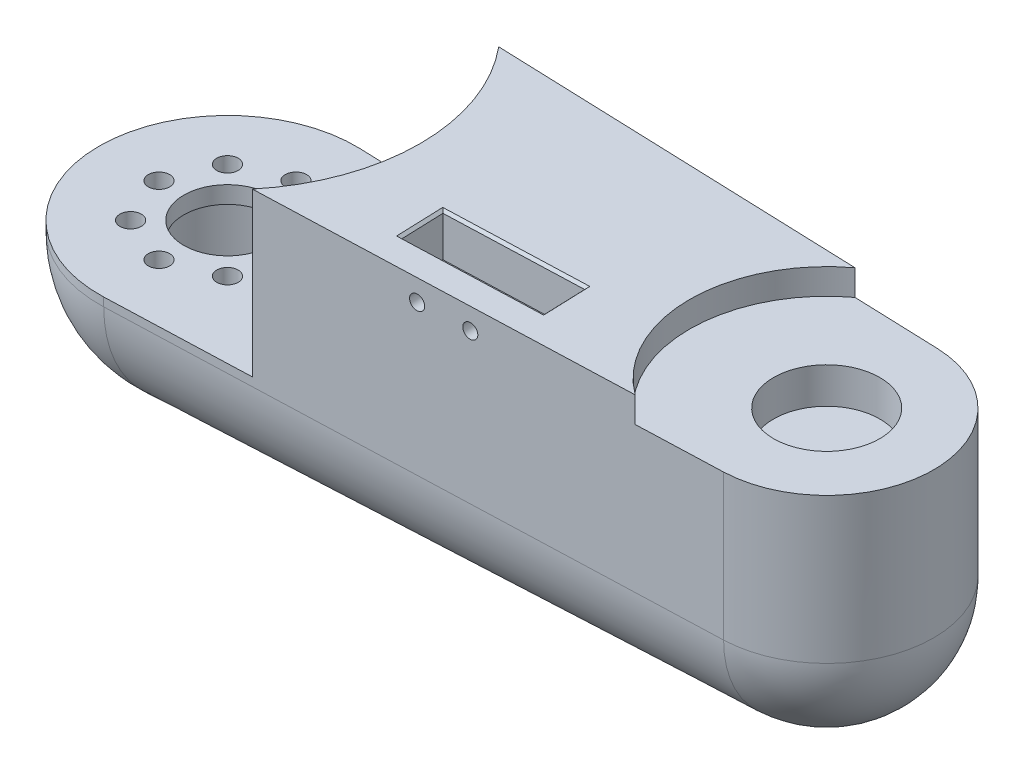
SolidWorks part; units mm, degrees
other "标注1"
sketch "草图20" plane through (82.5, 15, -19.5959) normal (0.2045, 0.9698, -0.1329) x (0.9753, -0.2135, -0.0568)
ref_plane "前视基准面" through (0, 0, 0) normal (0, 0, 1) x (1, 0, 0)
ref_plane "上视基准面" through (0, 0, 0) normal (0, 1, 0) x (1, 0, 0)
ref_plane "右视基准面" through (0, 0, 0) normal (1, 0, 0) x (0, 0, -1)
other "Configuration Table"
sketch "草图1" plane through (0, 0, 0) normal (0, 1, 0) x (1, 0, 0)
  line L2 (0.5357, -14.9904) -> (70.4464, -12.492)
  line L4 (-15, 0) -> (82.5, 0)
  arc A1 (70.4464, -12.492) -> (82.5, 0) centre (70, 0) ccw
  arc A3 (-15, 0) -> (0.5357, -14.9904) centre (0, 0) ccw
  dimension "D1" = 15
  dimension "D2" = 70
  dimension "D3" = 25
ref_axis "基准轴1" through (70, 0, 0) along (-1, 0, 0)
sketch "草图2" plane through (0, 0, 0) normal (0, 1, 0) x (1, 0, 0)
  line L0 (0.5357, 14.9904) -> (70.4464, 12.492)
  line L2 (0.5357, -14.9904) -> (70.4464, -12.492)
  line L3 (82.5, 0) -> (-15, 0)
  line L4 (0.5357, -14.9904) -> (70.4464, -12.492)
  line L5 (82.5, 0) -> (-15, 0)
  arc A2 (70.4464, -12.492) -> (82.5, 0) centre (70, 0) ccw
  arc A3 (-15, 0) -> (0.5357, -14.9904) centre (0, 0) ccw
  arc A4 (70.4464, -12.492) -> (70.4464, 12.492) centre (70, 0) ccw
  arc A5 (0.5357, 14.9904) -> (0.5357, -14.9904) centre (0, 0) ccw
  dimension "D1" = 0
extrude "凸台-拉伸1" add sketch "草图2" along normal blind 20 contours L0 A5 L5 A4 | L5 A5 L4 A4
revolve "旋转1" add sketch "草图1" angle 180 about axis through (70, 0, 0) along (-1, 0, 0)
sketch "草图3" plane through (0, 20, 0) normal (0, 1, 0) x (1, 0, 0)
  line L2 (70.4464, 12.492) -> (0.5357, 14.9904)
  line L3 (0.5357, -14.9904) -> (70.4464, -12.492)
  line L4 (17.2955, 14.3915) -> (0.5357, 14.9904)
  line L5 (0.5357, -14.9904) -> (17.2955, -14.3915)
  arc A0 (17.2955, -14.3915) -> (17.2955, 14.3915) centre (0, 0) ccw
  arc A3 (0.5357, 14.9904) -> (0.5357, -14.9904) centre (0, 0) ccw
  arc A4 (70.4464, -12.492) -> (70.4464, 12.492) centre (70, 0) ccw
  arc A5 (0.5357, 14.9904) -> (0.5357, -14.9904) centre (0, 0) ccw
  dimension "D1" = 45
  dimension "D2" = 0
extrude "切除-拉伸1" cut sketch "草图3" against normal blind 19
sketch "草图4" plane through (0, 1, 0) normal (0, 1, 0) x (1, 0, 0)
  circle A0 centre (0, 0) radius 10
  circle A1 centre (8, 0) radius 1.25
  circle A2 centre (5.6569, -5.6569) radius 1.25
  circle A3 centre (0, -8) radius 1.25
  circle A4 centre (-5.6569, -5.6569) radius 1.25
  circle A5 centre (-8, 0) radius 1.25
  circle A6 centre (-5.6569, 5.6569) radius 1.25
  circle A7 centre (0, 8) radius 1.25
  circle A8 centre (5.6569, 5.6569) radius 1.25
  circle A9 centre (0, 0) radius 5.1
  point P22 (0, 0)
  dimension "D1" = 20
  dimension "D3" = 2.5
  dimension "D5" = 10.2
  dimension "D2" = 8
  dimension "D4" = 8
ref_plane "基准面1" through (0, -1, 0) normal (0, 1, 0) x (1, 0, 0)
sketch "草图5" plane through (0, -1, 0) normal (0, 1, 0) x (1, 0, 0)
  circle A0 centre (0, 0) radius 10 construction
  circle A1 centre (0, 0) radius 10
extrude "切除-拉伸2" cut sketch "草图5" against normal through all
extrude "切除-拉伸3" cut sketch "草图4" against normal through all contours A1 | A2 | A3 | A4 | A5 | A8 | A6 | A7 | A9
sketch "草图11" plane through (0, 20, 0) normal (0, 1, 0) x (1, 0, 0)
  line L0 (70, 0) -> (93.8641, 0) construction
  line L1 (17.2955, 14.3915) -> (70.4464, 12.492) construction
  line L2 (17.2955, -14.3915) -> (70.4464, -12.492) construction
  line L3 (60.4653, 12.8487) -> (70.4464, 12.492)
  line L4 (70.4464, -12.492) -> (60.4653, -12.8487)
  arc A0 (70.4464, -12.492) -> (70.4464, 12.492) centre (70, 0) ccw construction
  arc A1 (70.4464, -12.492) -> (70.4464, 12.492) centre (70, 0) ccw
  arc A2 (60.4653, 12.8487) -> (60.4653, -12.8487) centre (70, 0) ccw
  dimension "D1" = 16
extrude "切除-拉伸5" cut sketch "草图11" against normal blind 3
sketch "草图6" plane through (0, 17, 0) normal (0, 1, 0) x (1, 0, 0)
  arc A0 (70.4464, 12.492) -> (70.4464, -12.492) centre (70, 0) ccw construction
  arc A1 (70.4464, 12.492) -> (70.4464, -12.492) centre (70, 0) ccw
  circle A2 centre (70, 0) radius 3
  circle A3 centre (70, 0) radius 6.2
  dimension "D1" = 6
  dimension "D2" = 12.4
extrude "切除-拉伸4" cut sketch "草图6" against normal blind 4.2 contours A3 A2
sketch "草图12" plane through (0, 20, 0) normal (0, 1, 0) x (1, 0, 0)
  line L1 (30.7605, -10.408) -> (46.7503, -9.8366)
  line L3 (46.7503, -9.8366) -> (46.5717, -4.8398)
  line L4 (60.4653, 12.8487) -> (17.2955, 14.3915)
  line L5 (17.2955, -14.3915) -> (60.4653, -12.8487)
  line L7 (17.2955, -14.3915) -> (60.4653, -12.8487)
  line L8 (46.5717, -4.8398) -> (30.5819, -5.4112)
  line L9 (30.5819, -5.4112) -> (30.7605, -10.408)
  line L10 (38.8804, -13.6201) -> (38.3703, 0.6528) construction
  arc A4 (60.4653, 12.8487) -> (60.4653, -12.8487) centre (70, 0) ccw
  arc A5 (17.2955, -14.3915) -> (17.2955, 14.3915) centre (0, 0) ccw
  dimension "D5" = 8
  dimension "D1" = 0
  dimension "D4" = 8
  dimension "D2" = 3.5
  dimension "D3" = 5
extrude "切除-拉伸6" cut sketch "草图12" against normal blind 5 contours L1 L10 L8 L9 | L10 L1 L3 L8
sketch "草图17" plane through (0.5357, 0, 14.9904) normal (0.0357, 0, 0.9994) x (0.9994, 0, -0.0357)
  line L4 (46.3692, 20) -> (30.3692, 20)
  line L5 (46.3692, 15) -> (46.3692, 20)
  line L6 (30.3692, 15) -> (46.3692, 15)
  line L7 (30.3692, 20) -> (30.3692, 15)
  line L8 (46.3692, 20) -> (30.3692, 20)
  line L9 (46.3692, 15) -> (46.3692, 20)
  line L10 (30.3692, 15) -> (46.3692, 15)
  line L11 (30.3692, 20) -> (30.3692, 15)
  point P4 (35.3692, 17.5)
  point P6 (41.3692, 17.5)
  point P9 (30.3692, 17.5)
  dimension "D2" = 5
  dimension "D3" = 5
  dimension "D1" = 0
hole_wizard "孔1" positions "草图18" profile "草图19" legacy
sketch "草图18" plane through (0.5357, 0, 14.9904) normal (0.0357, 0, 0.9994) x (0.9994, 0, -0.0357)
  point P0 (35.3692, 17.5)
  point P3 (41.3692, 17.5)
sketch "草图19" plane through (35.8823, 17.5, 13.7272) normal (0, 1, 0) x (0.9994, 0, -0.0357)
  line L0 (0, 0) -> (0, 3.5)
  line L1 (0, 3.5) -> (0.85, 3.5)
  line L2 (0.85, 3.5) -> (0.85, 0)
  line L3 (0.85, 0) -> (0, 0)
  line L4 (0, 110) -> (0, -10) construction
  dimension "直径" = 1.7
  dimension "深度" = 3.5
chamfer "倒角1" distance 0.3 angle 45 4 edges at (46.661, 20, 7.3382) (38.7554, 20, 10.1223) (30.6712, 20, 7.9096) (38.5768, 20, 5.1255)
